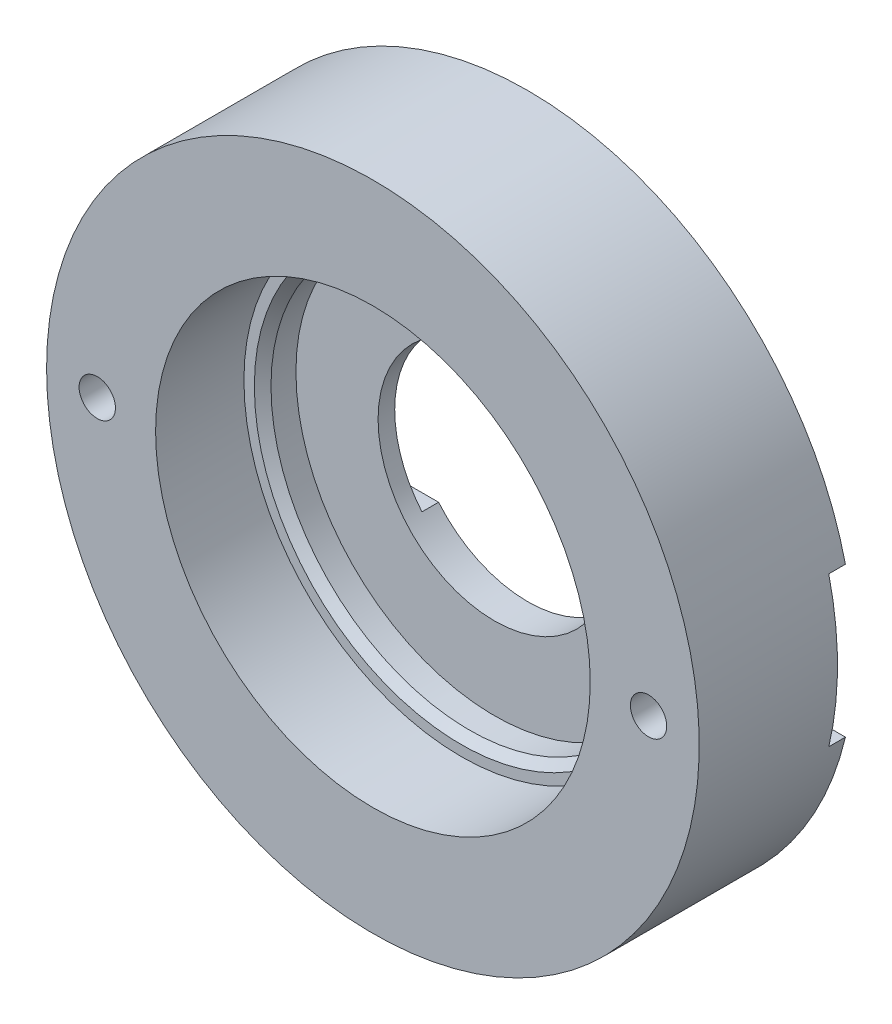
SolidWorks part; units mm, degrees
ref_plane "Front Plane" through (0, 0, 0) normal (0, 0, 1) x (1, 0, 0)
ref_plane "Top Plane" through (0, 0, 0) normal (0, 1, 0) x (1, 0, 0)
ref_plane "Right Plane" through (0, 0, 0) normal (1, 0, 0) x (0, 0, -1)
sketch "Sketch1" plane through (0, 0, 0) normal (0, 1, 0) x (1, 0, 0)
  line L0 (0, 25.4113) -> (0, -24.5124) construction
  line L2 (-7, 3.5255) -> (-19.6178, 3.5255)
  line L3 (-7, 3.5255) -> (-7, 1.5255)
  line L4 (-7, 1.5255) -> (-19.6178, 1.5255)
  line L5 (-19.6178, 3.5255) -> (-19.6178, 1.5255)
  line L6 (-11.938, 1.5255) -> (-19.6178, 1.5255)
  line L7 (-11.938, 1.5255) -> (-11.938, -0.4745)
  line L8 (-11.938, -0.4745) -> (-19.6178, -0.4745)
  line L9 (-19.6178, 1.5255) -> (-19.6178, -0.4745)
  line L10 (-13.0646, -0.4745) -> (-19.6178, -0.4745)
  line L11 (-13.0646, -0.4745) -> (-13.0646, -5.7845)
  line L12 (-13.0646, -5.7845) -> (-19.6178, -5.7845)
  line L13 (-19.6178, -0.4745) -> (-19.6178, -5.7845)
  dimension "D1" = 7
  dimension "D2" = 2
  dimension "D3" = 2
  dimension "D4" = 5.31
  dimension "D5" = 11.938
  dimension "D6" = 6.5532
revolve "Revolve1" add sketch "Sketch1" angle 360 about L0
sketch "Sketch2" plane through (0, 0, -3.5255) normal (0, 0, -1) x (-1, 0, 0)
  line L0 (-19.6178, 0) -> (19.6178, 0) construction
  line L1 (0, -19.6178) -> (0, 19.6178) construction
  circle A0 centre (0, 0) radius 19.6178 construction
  circle A1 centre (16.57, 0) radius 1.0922
  circle A2 centre (-16.57, 0) radius 1.0922
  point P11 (0, 0)
  dimension "D1" = 2.1844
  dimension "D3" = 16.57
extrude "Cut-Extrude1" cut sketch "Sketch2" against normal through all
sketch "Sketch3" plane through (0, 0, -3.5255) normal (0, 0, -1) x (-1, 0, 0)
  line L0 (19.6178, 0) -> (-19.6178, 0) construction
  line L1 (0, 19.6178) -> (0, -19.6178) construction
  line L3 (-22.5619, 4.5) -> (22.5619, 4.5)
  line L4 (-22.5619, 4.5) -> (-22.5619, -4.5)
  line L5 (-22.5619, -4.5) -> (22.5619, -4.5)
  line L6 (22.5619, 4.5) -> (22.5619, -4.5)
  line L7 (-22.5619, 4.5) -> (22.5619, -4.5) construction
  line L8 (-22.5619, -4.5) -> (22.5619, 4.5) construction
  circle A0 centre (0, 0) radius 19.6178 construction
  point P7 (0, 0)
  dimension "D1" = 9
extrude "Cut-Extrude2" cut sketch "Sketch3" against normal blind 1
chamfer "Chamfer1" distance 0.5 angle 45 1 edges at (-11.938, 0, 0.4745)
